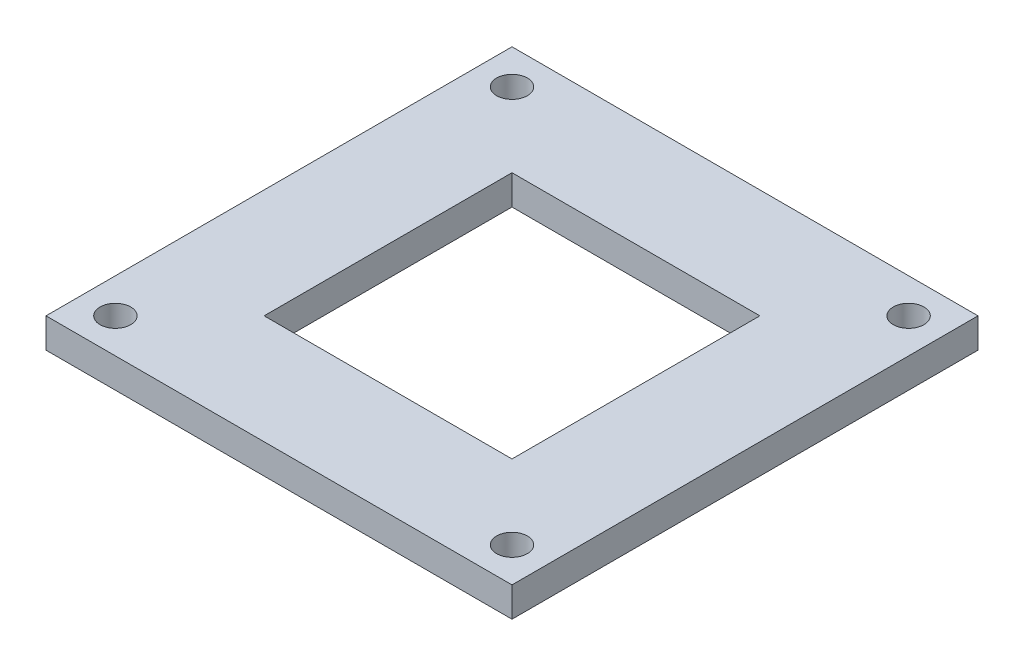
SolidWorks part; units mm, degrees
ref_plane "前视基准面" through (0, 0, 0) normal (0, 0, 1) x (1, 0, 0)
ref_plane "上视基准面" through (0, 0, 0) normal (0, 1, 0) x (1, 0, 0)
ref_plane "右视基准面" through (0, 0, 0) normal (1, 0, 0) x (0, 0, -1)
sketch "草图1" plane through (0, 0, 0) normal (0, 1, 0) x (1, 0, 0)
  line L1 (-23.5, 23.5) -> (23.5, 23.5)
  line L2 (-23.5, 23.5) -> (-23.5, -23.5)
  line L3 (-23.5, -23.5) -> (23.5, -23.5)
  line L4 (23.5, 23.5) -> (23.5, -23.5)
  line L5 (-23.5, 23.5) -> (23.5, -23.5) construction
  line L6 (-23.5, -23.5) -> (23.5, 23.5) construction
  point P0 (0, 0)
  dimension "D1" = 47
  dimension "D2" = 47
extrude "凸台-拉伸1" add sketch "草图1" along normal blind 3
sketch "草图2" plane through (0, 3, 0) normal (0, 1, 0) x (1, 0, 0)
  line L1 (-12.5, -12.5) -> (12.5, -12.5)
  line L2 (-12.5, -12.5) -> (-12.5, 12.5)
  line L3 (-12.5, 12.5) -> (12.5, 12.5)
  line L4 (12.5, -12.5) -> (12.5, 12.5)
  line L5 (-12.5, -12.5) -> (12.5, 12.5) construction
  line L6 (-12.5, 12.5) -> (12.5, -12.5) construction
  point P0 (0, 0)
  dimension "D1" = 25
  dimension "D2" = 25
extrude "切除-拉伸1" cut sketch "草图2" against normal blind 3
sketch "草图3" plane through (0, 0, 0) normal (0, -1, 0) x (1, 0, 0)
  line L0 (-20, 0) -> (20, 0) construction
  line L1 (-20, 20) -> (20, 20) construction
  line L2 (-20, 20) -> (-20, -20) construction
  line L3 (-20, -20) -> (20, -20) construction
  line L4 (20, 20) -> (20, -20) construction
  line L5 (-20, 20) -> (20, -20) construction
  line L6 (-20, -20) -> (20, 20) construction
  line L7 (0, 20) -> (0, -20) construction
  circle A0 centre (20, 20) radius 1.55
  circle A1 centre (-20, 20) radius 1.55
  circle A2 centre (20, -20) radius 1.55
  circle A3 centre (-20, -20) radius 1.55
  point P0 (0, 0)
  dimension "D3" = 3.1
  dimension "D1" = 40
  dimension "D2" = 40
extrude "切除-拉伸2" cut sketch "草图3" against normal blind 3
